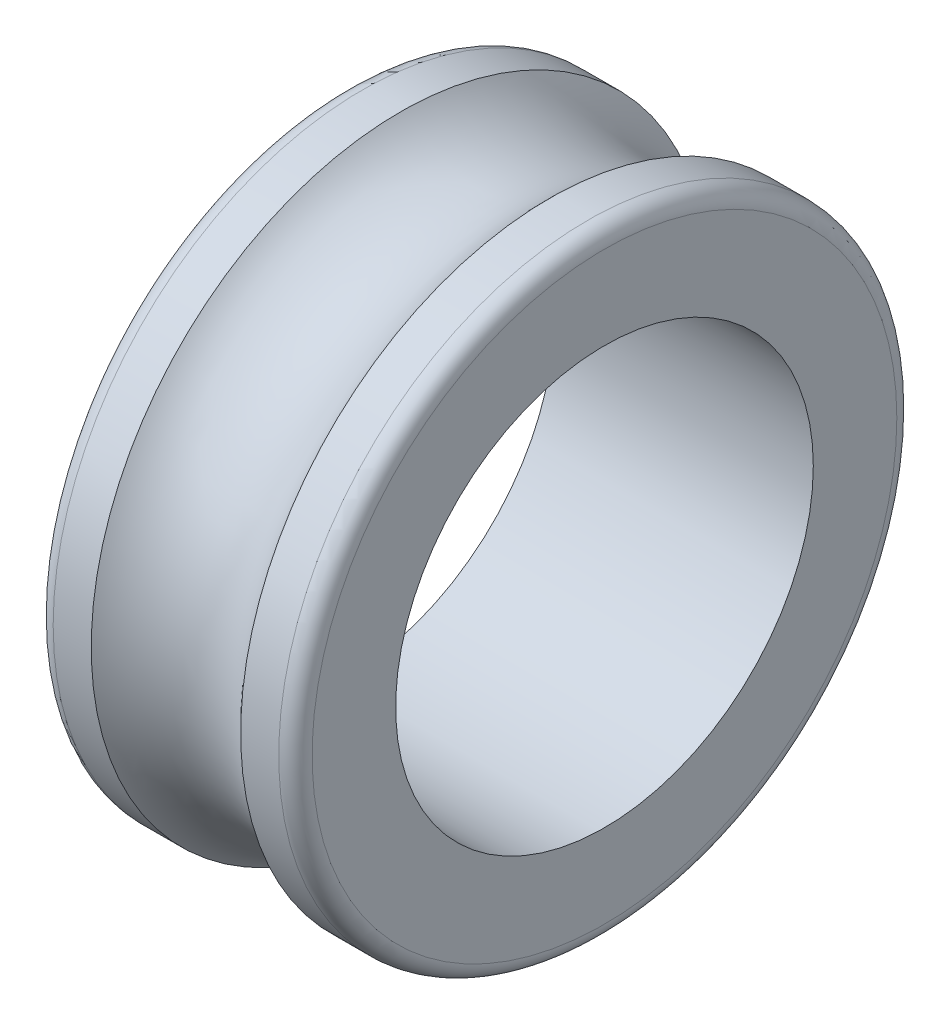
SolidWorks part; units mm, degrees
ref_plane "前视基准面" through (0, 0, 0) normal (0, 0, 1) x (1, 0, 0)
ref_plane "上视基准面" through (0, 0, 0) normal (0, 1, 0) x (1, 0, 0)
ref_plane "右视基准面" through (0, 0, 0) normal (1, 0, 0) x (0, 0, -1)
sketch "草图1" plane through (0, 0, 0) normal (0, 0, 1) x (1, 0, 0)
  line L0 (34.9574, 0) -> (0, 0) construction
  line L1 (0, 0) -> (0, 33) construction
  line L2 (8.9443, 37) -> (15.5, 37)
  line L3 (-15.5, 37) -> (-8.9443, 37)
  line L4 (-15.5, 37) -> (-15.5, 25)
  line L5 (-15.5, 25) -> (15.5, 25)
  line L6 (15.5, 37) -> (15.5, 25)
  line L7 (-15.5, 37) -> (15.5, 25) construction
  line L8 (-15.5, 25) -> (15.5, 37) construction
  line L9 (0, 37) -> (0, 42.5426) construction
  arc A0 (-8.9443, 37) -> (8.9443, 37) centre (0, 45) ccw
  point P4 (0, 31)
  dimension "D4" = 12
  dimension "D1" = 31
  dimension "D2" = 12
  dimension "D3" = 37
  dimension "D5" = 8
revolve "旋转1" add sketch "草图1" angle 360 about L0
fillet "圆角1" radius 2 2 edges at (-15.5, 0, -37) (15.5, 0, -37)
